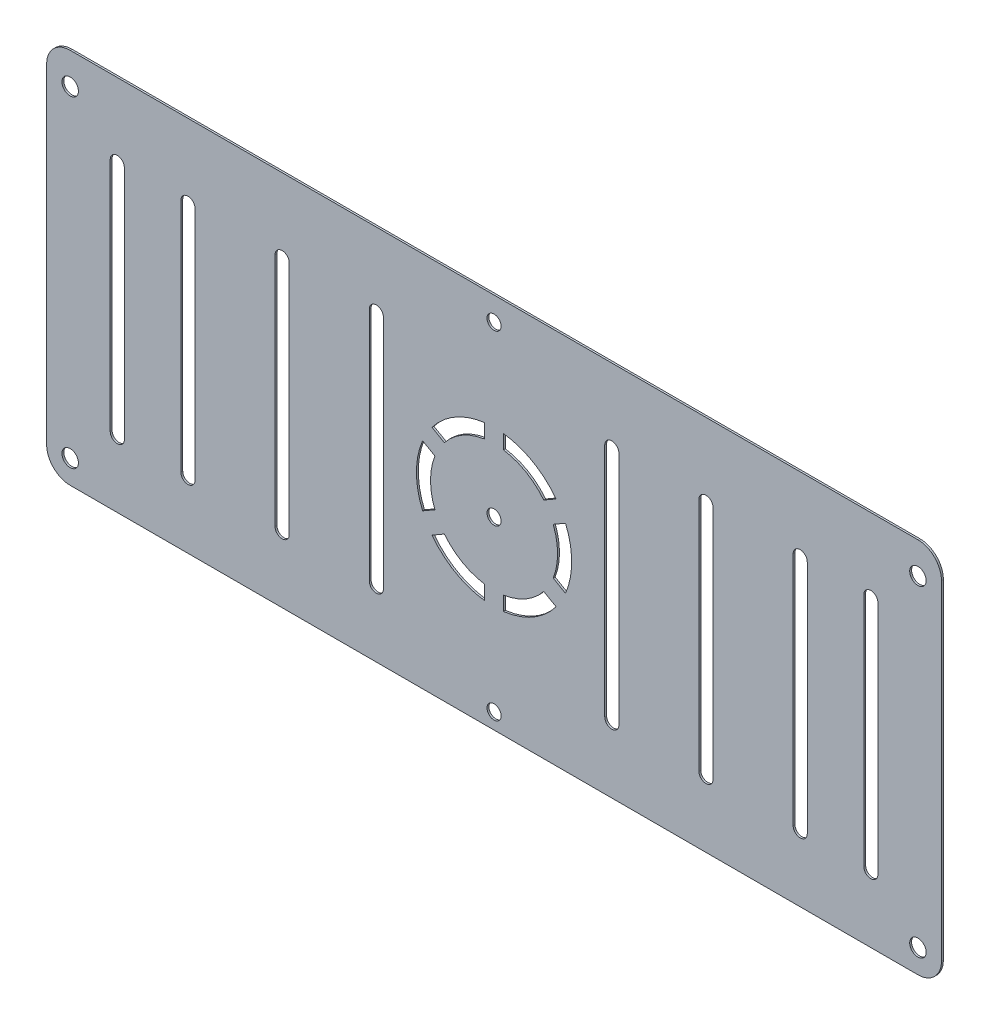
SolidWorks part; units mm, degrees
ref_plane "前视基准面" through (0, 0, 0) normal (0, 0, 1) x (1, 0, 0)
ref_plane "上视基准面" through (0, 0, 0) normal (0, 1, 0) x (1, 0, 0)
ref_plane "右视基准面" through (0, 0, 0) normal (1, 0, 0) x (0, 0, -1)
other "Configuration Table"
sketch "草图1" plane through (0, 0, 0) normal (0, 0, 1) x (1, 0, 0)
  line L0 (0, 0) -> (0, -50000) construction
  line L1 (-90, 40.8289) -> (90, 40.8289)
  line L2 (-95, 35.8289) -> (-95, -34.1711)
  line L3 (-90, -39.1711) -> (90, -39.1711)
  line L4 (95, 35.8289) -> (95, -34.1711)
  line L7 (0, 0) -> (50000, 0) construction
  line L18 (-45, -25) -> (-45, 25) construction
  line L19 (-46.5, -25) -> (-46.5, 25)
  line L20 (-43.5, -25) -> (-43.5, 25)
  line L21 (65, -25) -> (65, 25) construction
  line L24 (63.5, -25) -> (63.5, 25)
  line L27 (-2, 16.3625) -> (-2, 13.3446)
  line L30 (2, 16.3625) -> (2, 13.3446)
  line L33 (13.1703, 9.9133) -> (10.5568, 8.4044)
  line L36 (15.1703, 6.4492) -> (12.5568, 4.9403)
  line L39 (66.5, -25) -> (66.5, 25)
  line L42 (-25, -25) -> (-25, 25) construction
  line L45 (45, -25) -> (45, 25) construction
  line L46 (43.5, -25) -> (43.5, 25)
  line L47 (46.5, -25) -> (46.5, 25)
  line L51 (-26.5, -25) -> (-26.5, 25)
  line L54 (-23.5, -25) -> (-23.5, 25)
  line L60 (15.1703, -6.4492) -> (12.5568, -4.9403)
  line L61 (13.1703, -9.9133) -> (10.5568, -8.4044)
  line L62 (2, -16.3625) -> (2, -13.3446)
  line L63 (-2, -16.3625) -> (-2, -13.3446)
  line L64 (-13.1703, -9.9133) -> (-10.5568, -8.4044)
  line L65 (-15.1703, -6.4492) -> (-12.5568, -4.9403)
  line L66 (-15.1703, 6.4492) -> (-12.5568, 4.9403)
  line L67 (-13.1703, 9.9133) -> (-10.5568, 8.4044)
  line L70 (-65, -25) -> (-65, 25) construction
  line L71 (-66.5, -25) -> (-66.5, 25)
  line L72 (-63.5, -25) -> (-63.5, 25)
  line L76 (80, -25) -> (80, 25) construction
  line L79 (25, -25) -> (25, 25) construction
  line L80 (23.5, -25) -> (23.5, 25)
  line L81 (26.5, -25) -> (26.5, 25)
  line L82 (-80, -25) -> (-80, 25) construction
  line L83 (-81.5, -25) -> (-81.5, 25)
  line L84 (-78.5, -25) -> (-78.5, 25)
  line L88 (81.5, -25) -> (81.5, 25)
  line L89 (78.5, -25) -> (78.5, 25)
  line L96 (35, -25) -> (35, 25) construction
  line L97 (33.5, -25) -> (33.5, 25) [skipped]
  line L98 (36.5, -25) -> (36.5, 25) [skipped]
  line L99 (-35, -25) -> (-35, 25) construction
  line L100 (-36.5, -25) -> (-36.5, 25) [skipped]
  line L101 (-33.5, -25) -> (-33.5, 25) [skipped]
  line L102 (35, -25) -> (35, 25) construction
  line L103 (33.5, -25) -> (33.5, 25) [skipped]
  line L104 (36.5, -25) -> (36.5, 25) [skipped]
  line L105 (-35, -25) -> (-35, 25) construction
  line L106 (-36.5, -25) -> (-36.5, 25) [skipped]
  line L107 (-33.5, -25) -> (-33.5, 25) [skipped]
  circle A0 centre (-90, -34.1711) radius 1.75
  arc A2 (-95, 35.8289) -> (-90, 40.8289) centre (-90, 35.8289) cw
  arc A3 (95, 35.8289) -> (90, 40.8289) centre (90, 35.8289) ccw
  arc A4 (95, -34.1711) -> (90, -39.1711) centre (90, -34.1711) cw
  arc A5 (-90, -39.1711) -> (-95, -34.1711) centre (-90, -34.1711) cw
  circle A6 centre (90, -34.1711) radius 1.75
  arc A16 (-46.5, -25) -> (-43.5, -25) centre (-45, -25) ccw
  arc A17 (-43.5, 25) -> (-46.5, 25) centre (-45, 25) ccw
  arc A34 (43.5, -25) -> (46.5, -25) centre (45, -25) ccw
  arc A35 (46.5, 25) -> (43.5, 25) centre (45, 25) ccw
  circle A44 centre (90, 34.1711) radius 1.75
  circle A45 centre (-90, 34.1711) radius 1.75
  circle A46 centre (0, 0) radius 1.5
  circle A50 centre (0, 35.8289) radius 1.5
  circle A51 centre (0, -35.8289) radius 1.5
  circle A57 centre (0, 0) radius 16.4842
  circle A58 centre (0, 0) radius 13.4937
  circle A59 centre (0, 0) radius 10
  circle A60 centre (0, 0) radius 13.4937
  circle A61 centre (0, 0) radius 16.4842
  circle A62 centre (0, 0) radius 1.5
  arc A65 (63.5, -25) -> (66.5, -25) centre (65, -25) ccw
  arc A66 (66.5, 25) -> (63.5, 25) centre (65, 25) ccw
  arc A67 (-26.5, -25) -> (-23.5, -25) centre (-25, -25) ccw
  arc A68 (-23.5, 25) -> (-26.5, 25) centre (-25, 25) ccw
  arc A71 (-66.5, -25) -> (-63.5, -25) centre (-65, -25) ccw
  arc A72 (-63.5, 25) -> (-66.5, 25) centre (-65, 25) ccw
  arc A77 (23.5, -25) -> (26.5, -25) centre (25, -25) ccw
  arc A78 (26.5, 25) -> (23.5, 25) centre (25, 25) ccw
  arc A79 (-81.5, -25) -> (-78.5, -25) centre (-80, -25) ccw
  arc A80 (-78.5, 25) -> (-81.5, 25) centre (-80, 25) ccw
  arc A83 (81.5, -25) -> (78.5, -25) centre (80, -25) cw
  arc A84 (78.5, 25) -> (81.5, 25) centre (80, 25) cw
  arc A95 (33.5, -25) -> (36.5, -25) centre (35, -25) ccw [skipped]
  arc A96 (36.5, 25) -> (33.5, 25) centre (35, 25) ccw [skipped]
  arc A97 (-36.5, -25) -> (-33.5, -25) centre (-35, -25) ccw [skipped]
  arc A98 (-33.5, 25) -> (-36.5, 25) centre (-35, 25) ccw [skipped]
  point P0 (0, 0)
  point P12 (35, 0)
  point P35 (65, 0)
  point P42 (-25, 0)
  point P48 (-35, 0)
  point P54 (-45, 0)
  point P70 (-65, 0)
  point P76 (-5, 0)
  point P83 (5, 0)
  point P92 (0, 0)
  point P97 (-15, 0)
  point P104 (80, 0)
  point P110 (25, 0)
  point P117 (45, 0)
  point P131 (-80, 0)
  point P138 (-75, 0)
  point P145 (75, 0)
  point P157 (15, 0)
  point P168 (-5, 0)
  point P175 (5, 0)
  point P182 (-15, 0)
  point P189 (15, 0)
  point P196 (-5, 0)
  point P203 (5, 0)
  point P210 (-15, 0)
  point P217 (15, 0)
  point P224 (-5, 0)
  point P231 (5, 0)
  point P238 (-15, 0)
  point P245 (15, 0)
  point P252 (-5, 0)
  point P259 (5, 0)
  point P266 (-15, 0)
  point P273 (15, 0)
  point P280 (-5, 0)
  point P287 (5, 0)
  point P294 (-15, 0)
  point P301 (15, 0)
  point P308 (-5, 0)
  point P315 (5, 0)
  point P322 (-15, 0)
  point P329 (15, 0)
  point P336 (-5, 0)
  point P343 (5, 0)
  point P350 (-15, 0)
  point P357 (15, 0)
  point P364 (-5, 0)
  point P371 (5, 0)
  point P378 (-15, 0)
  point P385 (15, 0)
  point P392 (-5, 0)
  point P399 (5, 0)
  point P406 (-15, 0)
  point P413 (15, 0)
  point P420 (-5, 0)
  point P427 (5, 0)
  point P434 (-15, 0)
  point P441 (15, 0)
  point P448 (-5, 0)
  point P455 (5, 0)
  point P462 (-15, 0)
  point P469 (15, 0)
  point P476 (-5, 0)
  point P483 (5, 0)
  point P490 (-15, 0)
  point P497 (15, 0)
  point P504 (-5, 0)
  point P511 (5, 0)
  point P518 (-15, 0)
  point P525 (15, 0)
  point P532 (-5, 0)
  point P539 (5, 0)
  point P546 (-15, 0)
  point P553 (15, 0)
  point P560 (-5, 0)
  point P567 (5, 0)
  point P574 (-15, 0)
  point P581 (15, 0)
  point P588 (-5, 0)
  point P595 (5, 0)
  point P602 (-15, 0)
  point P609 (15, 0)
  point P612 (35, 0)
  point P619 (-35, 0)
  point P626 (35, 0)
  point P633 (-35, 0)
  dimension "D3" = 3.5
  dimension "D7" = 3
  dimension "D9" = 5
  dimension "D10" = 5
  dimension "D11" = 5
  dimension "D18" = 3
  dimension "D16" = 20
  dimension "D2" = 80
  dimension "D4" = 90
  dimension "D5" = 5
  dimension "D6" = 3
  dimension "D8" = 3
  dimension "D12" = 190
  dimension "D14" = 50
  dimension "D15" = 50
  dimension "D19" = 90
  dimension "D17" = 4
  dimension "D21" = 6
extrude "凸台-拉伸1" add sketch "草图1" along normal blind 0.4
sketch "草图2" plane through (0, 0, 0.4) normal (0, 0, 1) x (1, 0, 0)
  circle A0 centre (0, 0) radius 1.5
  dimension "D1" = 3
extrude "切除-拉伸1" cut sketch "草图2" against normal blind 10
